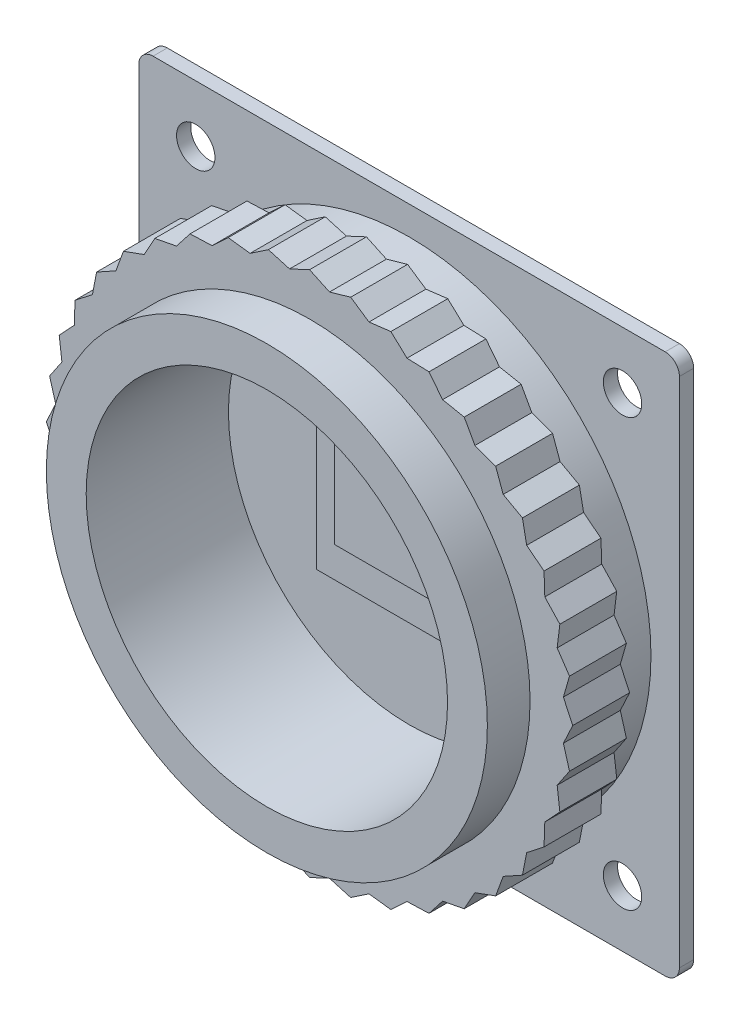
SolidWorks part; units mm, degrees
ref_plane "Front Plane" through (0, 0, 0) normal (0, 0, 1) x (1, 0, 0)
ref_plane "Top Plane" through (0, 0, 0) normal (0, 1, 0) x (1, 0, 0)
ref_plane "Right Plane" through (0, 0, 0) normal (1, 0, 0) x (0, 0, -1)
sketch "Sketch1" plane through (0, 0, 0) normal (0, 0, 1) x (1, 0, 0)
  line L0 (1, 0) -> (37, 0)
  line L1 (38, 1) -> (38, 37)
  line L2 (37, 38) -> (1, 38)
  line L3 (0, 37) -> (0, 1)
  arc A0 (37, 0) -> (38, 1) centre (37, 1) ccw
  arc A1 (38, 37) -> (37, 38) centre (37, 37) ccw
  arc A2 (1, 38) -> (0, 37) centre (1, 37) ccw
  arc A3 (0, 1) -> (1, 0) centre (1, 1) ccw
extrude "PCB" add sketch "Sketch1" along normal blind 1
ref_plane "Plane_z1" through (0, 0, 1) normal (0, 0, 1) x (1, 0, 0)
sketch "Sketch2" plane through (0, 0, 1) normal (0, 0, 1) x (1, 0, 0)
  line L1 (13.5, 13.5) -> (24.5, 13.5)
  line L2 (13.5, 13.5) -> (13.5, 24.5)
  line L3 (13.5, 24.5) -> (24.5, 24.5)
  line L4 (24.5, 13.5) -> (24.5, 24.5)
extrude "Sensor" add sketch "Sketch2" along normal blind 1
ref_plane "Plane_z2" through (0, 0, 2) normal (0, 0, 1) x (1, 0, 0)
sketch "Sketch3" plane through (0, 0, 2) normal (0, 0, 1) x (1, 0, 0)
  line L1 (15.05, 15.95) -> (22.95, 15.95)
  line L2 (15.05, 15.95) -> (15.05, 22.05)
  line L3 (15.05, 22.05) -> (22.95, 22.05)
  line L4 (22.95, 15.95) -> (22.95, 22.05)
extrude "Sensor_glass" add sketch "Sketch3" along normal blind 0.3
sketch "Sketch4" plane through (0, 0, 1) normal (0, 0, 1) x (1, 0, 0)
  circle A0 centre (19, 19) radius 17
  circle A1 centre (19, 19) radius 12.7
extrude "Mount_base" add sketch "Sketch4" along normal blind 3
ref_plane "Plane_z4" through (0, 0, 4) normal (0, 0, 1) x (1, 0, 0)
sketch "Sketch5" plane through (0, 0, 4) normal (0, 0, 1) x (1, 0, 0)
  line L0 (37.5, 19) -> (36.8448, 20.4044)
  line L1 (36.8448, 20.4044) -> (37.2722, 21.894)
  line L2 (37.2722, 21.894) -> (36.4054, 23.1787)
  line L3 (36.4054, 23.1787) -> (36.5945, 24.7168)
  line L4 (36.5945, 24.7168) -> (35.5374, 25.85)
  line L5 (35.5374, 25.85) -> (35.4836, 27.3988)
  line L6 (35.4836, 27.3988) -> (34.2623, 28.3527)
  line L7 (34.2623, 28.3527) -> (33.9668, 29.874)
  line L8 (33.9668, 29.874) -> (32.6113, 30.6251)
  line L9 (32.6113, 30.6251) -> (32.0815, 32.0815)
  line L10 (32.0815, 32.0815) -> (30.6251, 32.6113)
  line L11 (30.6251, 32.6113) -> (29.874, 33.9668)
  line L12 (29.874, 33.9668) -> (28.3527, 34.2623)
  line L13 (28.3527, 34.2623) -> (27.3988, 35.4836)
  line L14 (27.3988, 35.4836) -> (25.85, 35.5374)
  line L15 (25.85, 35.5374) -> (24.7168, 36.5945)
  line L16 (24.7168, 36.5945) -> (23.1787, 36.4054)
  line L17 (23.1787, 36.4054) -> (21.894, 37.2722)
  line L18 (21.894, 37.2722) -> (20.4044, 36.8448)
  line L19 (20.4044, 36.8448) -> (19, 37.5)
  line L20 (19, 37.5) -> (17.5956, 36.8448)
  line L21 (17.5956, 36.8448) -> (16.106, 37.2722)
  line L22 (16.106, 37.2722) -> (14.8213, 36.4054)
  line L23 (14.8213, 36.4054) -> (13.2832, 36.5945)
  line L24 (13.2832, 36.5945) -> (12.15, 35.5374)
  line L25 (12.15, 35.5374) -> (10.6012, 35.4836)
  line L26 (10.6012, 35.4836) -> (9.6473, 34.2623)
  line L27 (9.6473, 34.2623) -> (8.126, 33.9668)
  line L28 (8.126, 33.9668) -> (7.3749, 32.6113)
  line L29 (7.3749, 32.6113) -> (5.9185, 32.0815)
  line L30 (5.9185, 32.0815) -> (5.3887, 30.6251)
  line L31 (5.3887, 30.6251) -> (4.0332, 29.874)
  line L32 (4.0332, 29.874) -> (3.7377, 28.3527)
  line L33 (3.7377, 28.3527) -> (2.5164, 27.3988)
  line L34 (2.5164, 27.3988) -> (2.4626, 25.85)
  line L35 (2.4626, 25.85) -> (1.4055, 24.7168)
  line L36 (1.4055, 24.7168) -> (1.5946, 23.1787)
  line L37 (1.5946, 23.1787) -> (0.7278, 21.894)
  line L38 (0.7278, 21.894) -> (1.1552, 20.4044)
  line L39 (1.1552, 20.4044) -> (0.5, 19)
  line L40 (0.5, 19) -> (1.1552, 17.5956)
  line L41 (1.1552, 17.5956) -> (0.7278, 16.106)
  line L42 (0.7278, 16.106) -> (1.5946, 14.8213)
  line L43 (1.5946, 14.8213) -> (1.4055, 13.2832)
  line L44 (1.4055, 13.2832) -> (2.4626, 12.15)
  line L45 (2.4626, 12.15) -> (2.5164, 10.6012)
  line L46 (2.5164, 10.6012) -> (3.7377, 9.6473)
  line L47 (3.7377, 9.6473) -> (4.0332, 8.126)
  line L48 (4.0332, 8.126) -> (5.3887, 7.3749)
  line L49 (5.3887, 7.3749) -> (5.9185, 5.9185)
  line L50 (5.9185, 5.9185) -> (7.3749, 5.3887)
  line L51 (7.3749, 5.3887) -> (8.126, 4.0332)
  line L52 (8.126, 4.0332) -> (9.6473, 3.7377)
  line L53 (9.6473, 3.7377) -> (10.6012, 2.5164)
  line L54 (10.6012, 2.5164) -> (12.15, 2.4626)
  line L55 (12.15, 2.4626) -> (13.2832, 1.4055)
  line L56 (13.2832, 1.4055) -> (14.8213, 1.5946)
  line L57 (14.8213, 1.5946) -> (16.106, 0.7278)
  line L58 (16.106, 0.7278) -> (17.5956, 1.1552)
  line L59 (17.5956, 1.1552) -> (19, 0.5)
  line L60 (19, 0.5) -> (20.4044, 1.1552)
  line L61 (20.4044, 1.1552) -> (21.894, 0.7278)
  line L62 (21.894, 0.7278) -> (23.1787, 1.5946)
  line L63 (23.1787, 1.5946) -> (24.7168, 1.4055)
  line L64 (24.7168, 1.4055) -> (25.85, 2.4626)
  line L65 (25.85, 2.4626) -> (27.3988, 2.5164)
  line L66 (27.3988, 2.5164) -> (28.3527, 3.7377)
  line L67 (28.3527, 3.7377) -> (29.874, 4.0332)
  line L68 (29.874, 4.0332) -> (30.6251, 5.3887)
  line L69 (30.6251, 5.3887) -> (32.0815, 5.9185)
  line L70 (32.0815, 5.9185) -> (32.6113, 7.3749)
  line L71 (32.6113, 7.3749) -> (33.9668, 8.126)
  line L72 (33.9668, 8.126) -> (34.2623, 9.6473)
  line L73 (34.2623, 9.6473) -> (35.4836, 10.6012)
  line L74 (35.4836, 10.6012) -> (35.5374, 12.15)
  line L75 (35.5374, 12.15) -> (36.5945, 13.2832)
  line L76 (36.5945, 13.2832) -> (36.4054, 14.8213)
  line L77 (36.4054, 14.8213) -> (37.2722, 16.106)
  line L78 (37.2722, 16.106) -> (36.8448, 17.5956)
  line L79 (36.8448, 17.5956) -> (37.5, 19)
  circle A0 centre (19, 19) radius 12.7
extrude "Lock_ring" add sketch "Sketch5" along normal blind 4
ref_plane "Plane_z8" through (0, 0, 8) normal (0, 0, 1) x (1, 0, 0)
sketch "Sketch6" plane through (0, 0, 8) normal (0, 0, 1) x (1, 0, 0)
  circle A0 centre (19, 19) radius 15.5
  circle A1 centre (19, 19) radius 12.7
extrude "CS_tube" add sketch "Sketch6" along normal blind 3
sketch "Sketch7" plane through (0, 0, 0) normal (0, 0, 1) x (1, 0, 0)
  line L1 (8.5, 0.75) -> (29.5, 0.75)
  line L2 (8.5, 0.75) -> (8.5, 6.25)
  line L3 (8.5, 6.25) -> (29.5, 6.25)
  line L4 (29.5, 0.75) -> (29.5, 6.25)
extrude "FFC_connector" add sketch "Sketch7" against normal blind 2.5
sketch "Sketch8" plane through (0, 0, 1) normal (0, 0, 1) x (1, 0, 0)
  circle A0 centre (4, 4) radius 1.35
  circle A1 centre (4, 34) radius 1.35
  circle A2 centre (34, 4) radius 1.35
  circle A3 centre (34, 34) radius 1.35
extrude "Holes" cut sketch "Sketch8" against normal blind 1
equation "\"pcb_t\"= 1.0mm"
equation "\"D1@PCB\" = \"pcb_t\""
